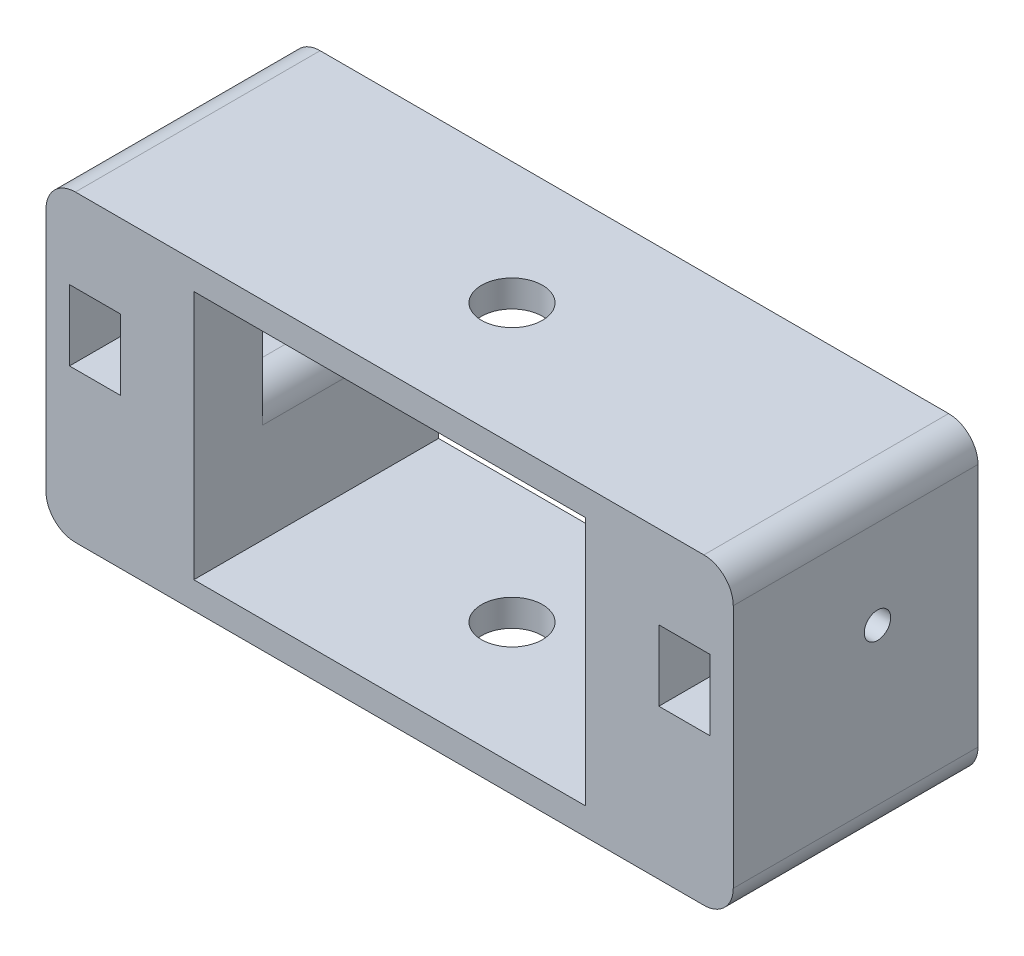
SolidWorks part; units mm, degrees
ref_plane "前视基准面" through (0, 0, 0) normal (0, 0, 1) x (1, 0, 0)
ref_plane "上视基准面" through (0, 0, 0) normal (0, 1, 0) x (1, 0, 0)
ref_plane "右视基准面" through (0, 0, 0) normal (1, 0, 0) x (0, 0, -1)
other "Configuration Table"
sketch "草图1" plane through (0, 0, 0) normal (0, 0, 1) x (1, 0, 0)
  line L1 (-35.1, 15.5) -> (35.1, 15.5)
  line L2 (-35.1, 15.5) -> (-35.1, -15.5)
  line L3 (-35.1, -15.5) -> (35.1, -15.5)
  line L4 (35.1, 15.5) -> (35.1, -15.5)
  line L5 (-35.1, 15.5) -> (35.1, -15.5) construction
  line L6 (-35.1, -15.5) -> (35.1, 15.5) construction
  point P0 (0, 0)
  dimension "D1" = 31
  dimension "D2" = 70.2
extrude "凸台-拉伸1" add sketch "草图1" along normal blind 25
sketch "草图2" plane through (0, 0, 25) normal (0, 0, 1) x (1, 0, 0)
  line L0 (0, -15.5) -> (0, 15.5) construction
  line L1 (-35.1, -15.5) -> (35.1, -15.5) construction
  line L2 (35.1, 15.5) -> (-35.1, 15.5) construction
  line L4 (-20, 12.75) -> (20, 12.75)
  line L5 (-20, 12.75) -> (-20, -12.75)
  line L6 (-20, -12.75) -> (20, -12.75)
  line L7 (20, 12.75) -> (20, -12.75)
  line L8 (-20, 12.75) -> (20, -12.75) construction
  line L9 (-20, -12.75) -> (20, 12.75) construction
  point P6 (0, 0)
  dimension "D1" = 25.5
  dimension "D2" = 40
extrude "切除-拉伸1" cut sketch "草图2" against normal blind 32
sketch "草图3" plane through (0, -15.5, 0) normal (0, -1, 0) x (1, 0, 0)
  line L0 (0, 0) -> (0, 25) construction
  line L1 (-35.1, 25) -> (35.1, 25) construction
  circle A0 centre (0, 12.5) radius 3.11
  dimension "D1" = 6.22
extrude "切除-拉伸2" cut sketch "草图3" against normal blind 41
sketch "草图4" plane through (0, 0, 0) normal (0, 0, -1) x (-1, 0, 0)
  line L0 (30.1, -0.0885) -> (30.1, 7.0915) construction
  line L1 (27.6, -0.0885) -> (32.6, -0.0885) construction
  line L2 (27.6, 7.0915) -> (32.6, 7.0915) construction
  line L3 (0, 15.5) -> (0, -28.8007) construction
  line L4 (32.7, -0.1885) -> (27.5, -0.1885)
  line L5 (32.7, -0.1885) -> (32.7, 7.0115)
  line L6 (32.7, 7.0115) -> (27.5, 7.0115)
  line L7 (27.5, -0.1885) -> (27.5, 7.0115)
  line L8 (32.7, -0.1885) -> (27.5, 7.0115) construction
  line L9 (32.7, 7.0115) -> (27.5, -0.1885) construction
  line L10 (-35.1, 15.5) -> (35.1, 15.5) construction
  line L11 (-32.7, 7.0115) -> (-27.5, -0.1885) construction
  line L12 (-32.7, -0.1885) -> (-27.5, 7.0115) construction
  line L13 (-30.1, -0.0885) -> (-30.1, 7.0915) construction
  line L14 (-27.5, -0.1885) -> (-27.5, 7.0115)
  line L15 (-32.7, 7.0115) -> (-27.5, 7.0115)
  line L16 (-32.7, -0.1885) -> (-32.7, 7.0115)
  line L17 (-32.7, -0.1885) -> (-27.5, -0.1885)
  point P6 (30.1, 3.4115)
  point P24 (-30.1, 3.4115)
  dimension "D1" = 5.2
  dimension "D2" = 7.2
extrude "切除-拉伸3" cut sketch "草图4" against normal blind 25
sketch "草图5" plane through (35.1, 0, 0) normal (1, 0, 0) x (0, 0, -1)
  circle A0 centre (-10.2689, 3.4115) radius 1.35
  dimension "D1" = 2.7
extrude "切除-拉伸4" cut sketch "草图5" against normal blind 122
fillet "圆角1" radius 3 4 edges at (35.1, -15.5, 12.5) (-35.1, -15.5, 12.5) (-35.1, 15.5, 12.5) (35.1, 15.5, 12.5)
sketch "草图6" plane through (0, 0, 0) normal (0, 0, -1) x (-1, 0, 0)
  line L0 (-23.75, 4.7615) -> (-23.75, 2.0615) construction
  line L1 (-20, 4.7615) -> (-27.5, 4.7615) construction
  line L2 (-27.5, 2.0615) -> (-20, 2.0615) construction
  line L3 (-26.1983, 3.4115) -> (-17.9042, 3.4115) construction
  line L4 (-25.323, 0.4115) -> (-25.323, 6.4115)
  line L5 (-25.323, 6.4115) -> (-20, 6.4115)
  line L6 (-20, -12.75) -> (-20, 12.75) construction
  line L7 (-25.323, 0.4115) -> (-20, 0.4115)
  line L8 (0, 0) -> (0, 23.7106) construction
  line L9 (26.1983, 3.4115) -> (17.9042, 3.4115) construction
  line L10 (23.75, 4.7615) -> (23.75, 2.0615) construction
  line L11 (25.323, 0.4115) -> (20, 0.4115)
  line L12 (25.323, 6.4115) -> (20, 6.4115)
  line L13 (25.323, 0.4115) -> (25.323, 6.4115)
  line L14 (-20, 6.4115) -> (-20, 0.4115)
  line L15 (20, 6.4115) -> (20, 0.4115)
  point P10 (-23.75, 3.4115)
  point P16 (-25.323, 3.4115)
  point P27 (25.323, 3.4115)
  dimension "D1" = 3
extrude "切除-拉伸5" cut sketch "草图6" against normal blind 18
fillet "圆角2" radius 3 4 edges at (-20, 0.4115, 9) (-20, 6.4115, 9) (20, 0.4115, 9) (20, 6.4115, 9)
